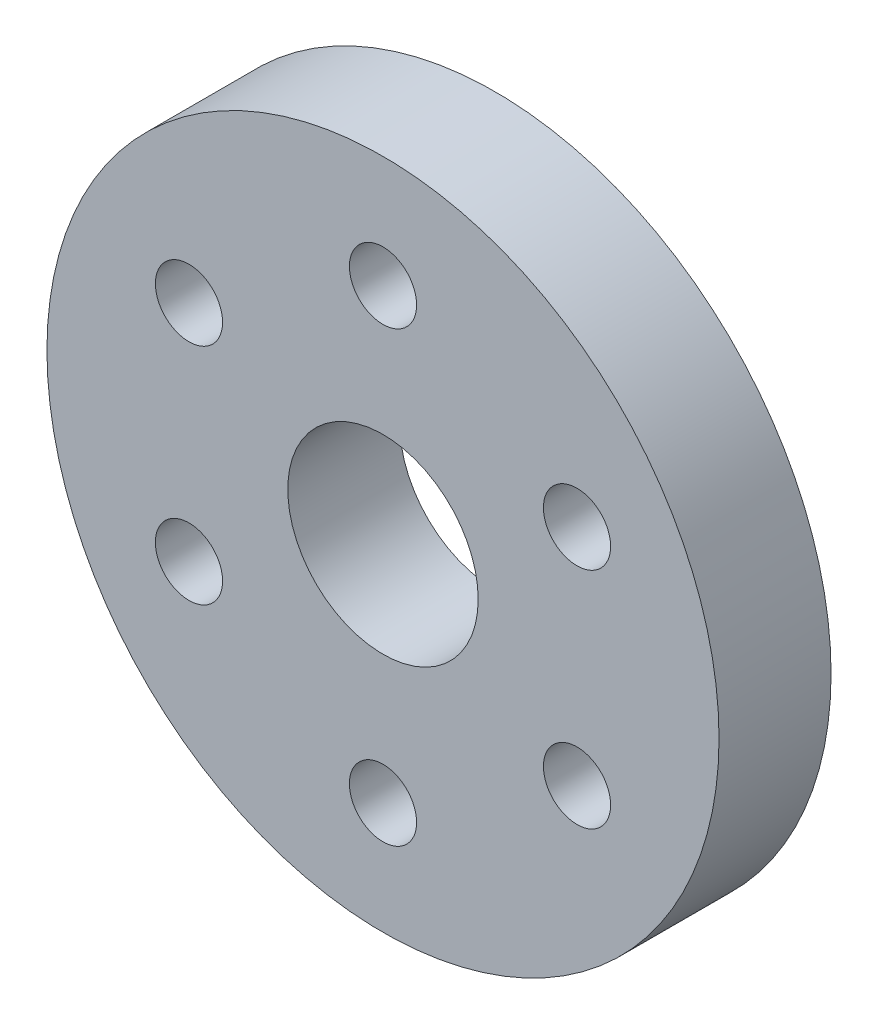
SolidWorks part; units mm, degrees
ref_plane "Plan de face" through (0, 0, 0) normal (0, 0, 1) x (1, 0, 0)
ref_plane "Plan de dessus" through (0, 0, 0) normal (0, 1, 0) x (1, 0, 0)
ref_plane "Plan de droite" through (0, 0, 0) normal (1, 0, 0) x (0, 0, -1)
sketch "Esquisse1" plane through (0, 0, 0) normal (0, 0, 1) x (1, 0, 0)
  line L0 (0, 0) -> (0, 15) construction
  circle A0 centre (0, 0) radius 15
  circle A1 centre (0, 0) radius 4.25
  circle A2 centre (0, 10) radius 1.5
  circle A3 centre (8.6603, 5) radius 1.5
  circle A4 centre (8.6603, -5) radius 1.5
  circle A5 centre (0, -10) radius 1.5
  circle A6 centre (-8.6603, -5) radius 1.5
  circle A7 centre (-8.6603, 5) radius 1.5
  point P7 (11.5386, -4.2539)
  point P8 (0, 0)
  point P13 (0, 0)
  dimension "D1" = 8.5
  dimension "D2" = 30
  dimension "D3" = 3
  dimension "D4" = 10
  dimension "D5" = 6
extrude "Boss.-Extru.1" add sketch "Esquisse1" along normal blind 5
